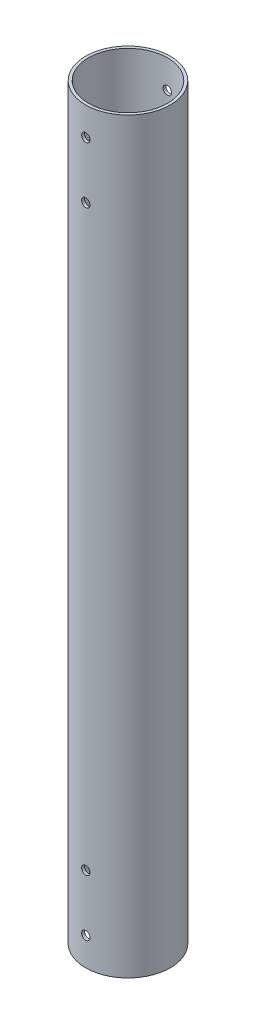
SolidWorks part; units mm, degrees
ref_plane "前基準面" through (0, 0, 0) normal (0, 0, 1) x (1, 0, 0)
ref_plane "上基準面" through (0, 0, 0) normal (0, 1, 0) x (1, 0, 0)
ref_plane "右基準面" through (0, 0, 0) normal (1, 0, 0) x (0, 0, -1)
sketch "草圖1" plane through (0, 0, 0) normal (0, 1, 0) x (1, 0, 0)
  circle A0 centre (0, 0) radius 15
  dimension "D1" = 30
extrude "填料-伸長1" add sketch "草圖1" along normal blind 265
sketch "草圖2" plane through (0, 0, 0) normal (0, 0, 1) x (1, 0, 0)
  line L0 (15, 265) -> (-15, 265) construction
  line L1 (-15, 132.5) -> (49985, 132.5) construction
  line L2 (-15, 265) -> (-15, 0) construction
  circle A0 centre (0, 255) radius 1.5
  circle A1 centre (0, 235) radius 1.5
  circle A2 centre (0, 10) radius 1.5
  circle A3 centre (0, 30) radius 1.5
  point P12 (-15, 132.5)
  dimension "D1" = 3
  dimension "D2" = 10
  dimension "D3" = 20
extrude "除料-伸長1" cut sketch "草圖2" against normal through all both and the other way through all
sketch "草圖3" plane through (0, 265, 0) normal (0, 1, 0) x (1, 0, 0)
  circle A2 centre (0, 0) radius 14
  circle A3 centre (0, 0) radius 14
  dimension "D1" = 1
extrude "除料-伸長2" cut sketch "草圖3" against normal up to next
